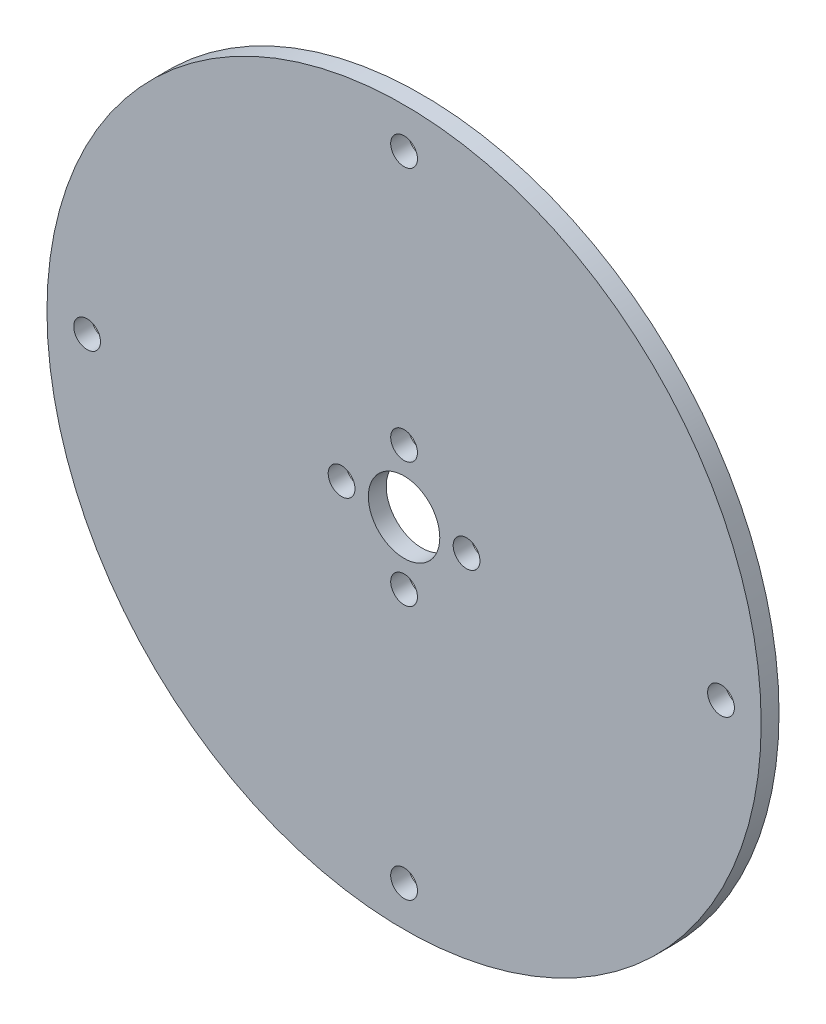
SolidWorks part; units mm, degrees
ref_plane "前视基准面" through (0, 0, 0) normal (0, 0, 1) x (1, 0, 0)
ref_plane "上视基准面" through (0, 0, 0) normal (0, 1, 0) x (1, 0, 0)
ref_plane "右视基准面" through (0, 0, 0) normal (1, 0, 0) x (0, 0, -1)
sketch "草图1" plane through (0, 0, 0) normal (0, 0, 1) x (1, 0, 0)
  line L0 (0, 0) -> (0, 20.8013) construction
  circle A0 centre (0, 0) radius 40
  circle A1 centre (0, 0) radius 7 construction
  circle A2 centre (0, 7) radius 1.5
  circle A3 centre (7, 0) radius 1.5
  circle A4 centre (0, -7) radius 1.5
  circle A5 centre (-7, 0) radius 1.5
  circle A6 centre (0, 0) radius 35.5 construction
  circle A7 centre (0, 35.5) radius 1.5
  circle A8 centre (35.5, 0) radius 1.5
  circle A9 centre (0, -35.5) radius 1.5
  circle A10 centre (-35.5, 0) radius 1.5
  circle A11 centre (0, 0) radius 4
  point P16 (0, 0)
  point P26 (0, 0)
  dimension "D1" = 80
  dimension "D2" = 14
  dimension "D3" = 3
  dimension "D5" = 71
  dimension "D6" = 3
  dimension "D8" = 8
  dimension "D4" = 4
  dimension "D7" = 4
extrude "凸台-拉伸1" add sketch "草图1" along normal blind 2
